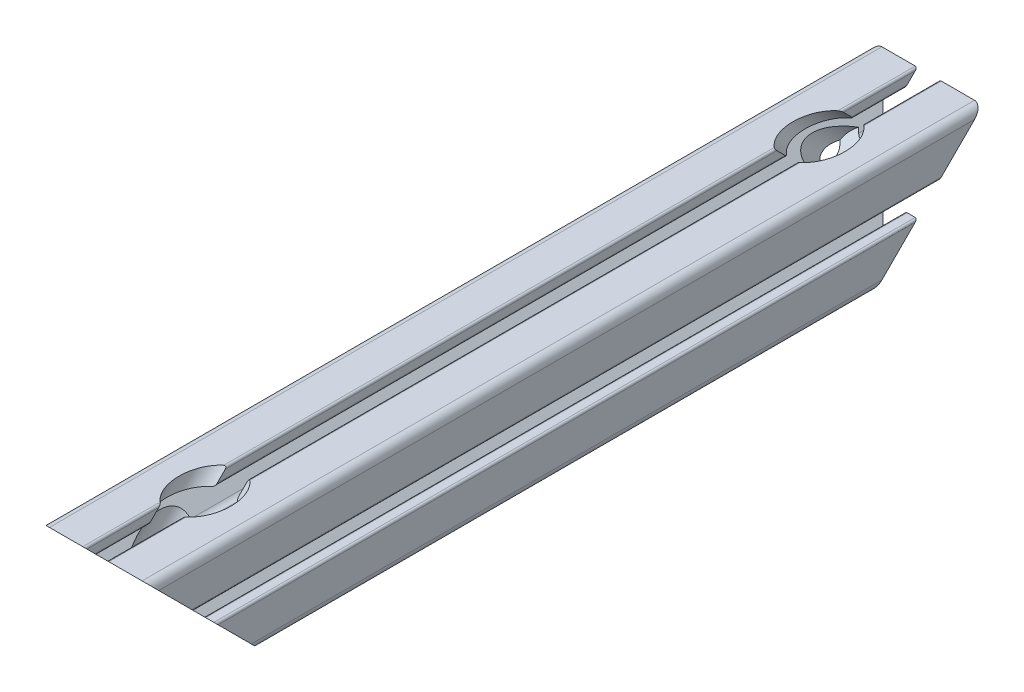
SolidWorks part; units mm, degrees
ref_plane "Front Plane" through (0, 0, 0) normal (0, 0, 1) x (1, 0, 0)
ref_plane "Top Plane" through (0, 0, 0) normal (0, 1, 0) x (1, 0, 0)
ref_plane "Right Plane" through (0, 0, 0) normal (1, 0, 0) x (0, 0, -1)
sketch "Sketch1" plane through (0, 0, 0) normal (0, 0, 1) x (1, 0, 0)
  line L2 (-20, 16.952) -> (-20, 4.7625)
  line L3 (-16.952, 20) -> (-4.7625, 20)
  line L4 (-4.0005, 19.238) -> (-4.0005, 16.2662)
  line L5 (-4.7625, 15.5042) -> (-10.2235, 15.5042)
  line L6 (-10.7623, 14.2034) -> (-5.194, 8.6351)
  line L7 (-14.2034, 10.7623) -> (-8.6351, 5.194)
  line L8 (-15.5042, 10.2235) -> (-15.5042, 4.7625)
  line L9 (-16.2662, 4.0005) -> (-19.238, 4.0005)
  line L11 (-3.0746, 7.7572) -> (3.0746, 7.7572)
  line L12 (-7.7572, 3.0746) -> (-7.7572, -3.0746)
  line L13 (16.2662, 4.0005) -> (19.238, 4.0005)
  line L14 (15.5042, 10.2235) -> (15.5042, 4.7625)
  line L15 (20, 16.952) -> (20, 4.7625)
  line L16 (16.952, 20) -> (4.7625, 20)
  line L17 (4.0005, 19.238) -> (4.0005, 16.2662)
  line L18 (4.7625, 15.5042) -> (10.2235, 15.5042)
  line L19 (7.7572, 3.0746) -> (7.7572, -3.0746)
  line L20 (10.7623, 14.2034) -> (5.194, 8.6351)
  line L21 (14.2034, 10.7623) -> (8.6351, 5.194)
  line L22 (-16.2662, -4.0005) -> (-19.238, -4.0005)
  line L23 (-15.5042, -10.2235) -> (-15.5042, -4.7625)
  line L24 (-14.2034, -10.7623) -> (-8.6351, -5.194)
  line L25 (-10.7623, -14.2034) -> (-5.194, -8.6351)
  line L26 (-4.7625, -15.5042) -> (-10.2235, -15.5042)
  line L27 (-4.0005, -19.238) -> (-4.0005, -16.2662)
  line L28 (-16.952, -20) -> (-4.7625, -20)
  line L29 (-20, -16.952) -> (-20, -4.7625)
  line L30 (20, -16.952) -> (20, -4.7625)
  line L31 (16.952, -20) -> (4.7625, -20)
  line L32 (4.0005, -19.238) -> (4.0005, -16.2662)
  line L33 (4.7625, -15.5042) -> (10.2235, -15.5042)
  line L34 (10.7623, -14.2034) -> (5.194, -8.6351)
  line L35 (14.2034, -10.7623) -> (8.6351, -5.194)
  line L36 (15.5042, -10.2235) -> (15.5042, -4.7625)
  line L37 (16.2662, -4.0005) -> (19.238, -4.0005)
  line L38 (-3.0746, -7.7572) -> (3.0746, -7.7572)
  circle A0 centre (0, 0) radius 3.4036
  arc A1 (-20, 16.952) -> (-16.952, 20) centre (-16.952, 16.952) cw
  arc A2 (-14.2034, 10.7623) -> (-15.5042, 10.2235) centre (-14.7422, 10.2235) ccw
  arc A3 (-10.2235, 15.5042) -> (-10.7623, 14.2034) centre (-10.2235, 14.7422) ccw
  arc A4 (-4.7625, 20) -> (-4.0005, 19.238) centre (-4.7625, 19.238) cw
  arc A5 (-20, 4.7625) -> (-19.238, 4.0005) centre (-19.238, 4.7625) ccw
  arc A6 (-15.5042, 4.7625) -> (-16.2662, 4.0005) centre (-16.2662, 4.7625) cw
  arc A7 (-4.0005, 16.2662) -> (-4.7625, 15.5042) centre (-4.7625, 16.2662) cw
  arc A8 (-3.0746, 7.7572) -> (-5.194, 8.6351) centre (-3.0746, 10.7544) cw
  arc A9 (-7.7572, 3.0746) -> (-8.6351, 5.194) centre (-10.7544, 3.0746) ccw
  arc A10 (15.5042, 4.7625) -> (16.2662, 4.0005) centre (16.2662, 4.7625) ccw
  arc A11 (20, 4.7625) -> (19.238, 4.0005) centre (19.238, 4.7625) cw
  arc A12 (20, 16.952) -> (16.952, 20) centre (16.952, 16.952) ccw
  arc A13 (4.7625, 20) -> (4.0005, 19.238) centre (4.7625, 19.238) ccw
  arc A14 (4.0005, 16.2662) -> (4.7625, 15.5042) centre (4.7625, 16.2662) ccw
  arc A15 (3.0746, 7.7572) -> (5.194, 8.6351) centre (3.0746, 10.7544) ccw
  arc A16 (7.7572, 3.0746) -> (8.6351, 5.194) centre (10.7544, 3.0746) cw
  arc A17 (14.2034, 10.7623) -> (15.5042, 10.2235) centre (14.7422, 10.2235) cw
  arc A18 (10.2235, 15.5042) -> (10.7623, 14.2034) centre (10.2235, 14.7422) cw
  arc A19 (-7.7572, -3.0746) -> (-8.6351, -5.194) centre (-10.7544, -3.0746) cw
  arc A20 (-3.0746, -7.7572) -> (-5.194, -8.6351) centre (-3.0746, -10.7544) ccw
  arc A21 (-4.0005, -16.2662) -> (-4.7625, -15.5042) centre (-4.7625, -16.2662) ccw
  arc A22 (-15.5042, -4.7625) -> (-16.2662, -4.0005) centre (-16.2662, -4.7625) ccw
  arc A23 (-20, -4.7625) -> (-19.238, -4.0005) centre (-19.238, -4.7625) cw
  arc A24 (-4.7625, -20) -> (-4.0005, -19.238) centre (-4.7625, -19.238) ccw
  arc A25 (-10.2235, -15.5042) -> (-10.7623, -14.2034) centre (-10.2235, -14.7422) cw
  arc A26 (-14.2034, -10.7623) -> (-15.5042, -10.2235) centre (-14.7422, -10.2235) cw
  arc A27 (-20, -16.952) -> (-16.952, -20) centre (-16.952, -16.952) ccw
  arc A28 (20, -16.952) -> (16.952, -20) centre (16.952, -16.952) cw
  arc A29 (14.2034, -10.7623) -> (15.5042, -10.2235) centre (14.7422, -10.2235) ccw
  arc A30 (10.2235, -15.5042) -> (10.7623, -14.2034) centre (10.2235, -14.7422) ccw
  arc A31 (4.7625, -20) -> (4.0005, -19.238) centre (4.7625, -19.238) cw
  arc A32 (20, -4.7625) -> (19.238, -4.0005) centre (19.238, -4.7625) ccw
  arc A33 (15.5042, -4.7625) -> (16.2662, -4.0005) centre (16.2662, -4.7625) cw
  arc A34 (4.0005, -16.2662) -> (4.7625, -15.5042) centre (4.7625, -16.2662) cw
  arc A35 (3.0746, -7.7572) -> (5.194, -8.6351) centre (3.0746, -10.7544) cw
  arc A36 (7.7572, -3.0746) -> (8.6351, -5.194) centre (10.7544, -3.0746) ccw
extrude "Boss-Extrude1" add sketch "Sketch1" along normal mid plane 304.8
sketch "Sketch2" plane through (0, 0, 0) normal (1, 0, 0) x (0, 0, -1)
  line L0 (-152.4, 20) -> (-152.4, -20)
  line L1 (-152.4, -20) -> (-112.4, -20)
  line L2 (-112.4, -20) -> (-152.4, 20)
  line L3 (0, 0) -> (0, 20) construction
  line L4 (-152.4, 20) -> (152.4, 20) construction
  line L5 (112.4, -20) -> (152.4, 20)
  line L6 (152.4, -20) -> (112.4, -20)
  line L7 (152.4, 20) -> (152.4, -20)
extrude "Cut-Extrude1" cut sketch "Sketch2" against normal through all and the other way through all
sketch "Sketch3" plane through (0, 0, 0) normal (1, 0, 0) x (0, 0, -1)
  line L0 (-152.4, -20) -> (-105.6825, 26.7175) construction
  line L1 (-105.6825, 26.7175) -> (-112.4, 33.435)
  line L2 (-112.4, 33.435) -> (-134.6627, 11.1723)
  line L3 (-134.6627, 11.1723) -> (-130.8797, 7.3893)
  line L4 (-130.8797, 7.3893) -> (-135.3345, 2.9345)
  line L5 (-135.3345, 2.9345) -> (-132.4, 0)
  line L6 (-112.4, -20) -> (-152.4, 20) construction
  line L7 (-98.965, 20) -> (-121.2277, -2.2627) construction
  line L8 (-152.4, 20) -> (152.4, 20) construction
  line L9 (-135.8036, 3.4036) -> (-128.9964, -3.4036) construction
  line L10 (-105.6825, 26.7175) -> (-132.4, 0)
  dimension "D1" = 8.3
  dimension "D2" = 19
  dimension "D3" = 6.3
revolve "Cut-Revolve1" cut sketch "Sketch3" angle 360 mid plane about L0
mirror "Mirror1" about plane through (0, 0, 0) normal (0, 0, 1) of "Cut-Revolve1"
